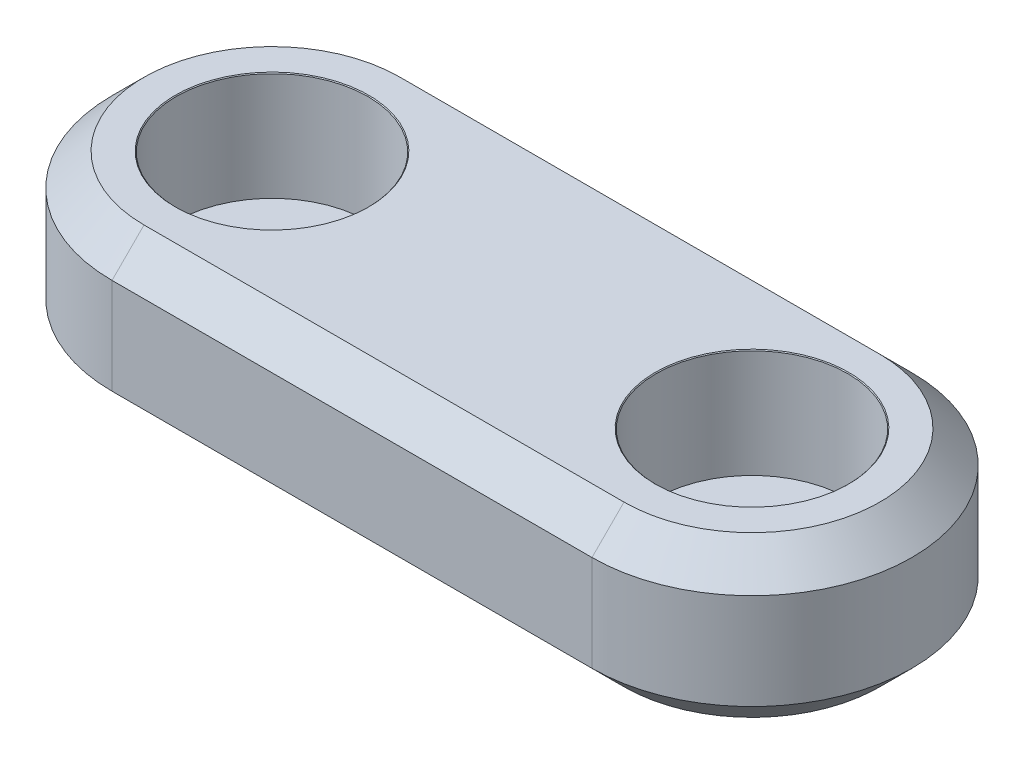
SolidWorks part; units mm, degrees
material "6061 Alloy"
ref_plane "Front Plane" through (0, 0, 0) normal (0, 0, 1) x (1, 0, 0)
ref_plane "Top Plane" through (0, 0, 0) normal (0, 1, 0) x (1, 0, 0)
ref_plane "Right Plane" through (0, 0, 0) normal (1, 0, 0) x (0, 0, -1)
sketch "Sketch1" plane through (0, 0, 0) normal (0, 1, 0) x (1, 0, 0)
  line L0 (-7.5, 0) -> (7.5, 0) construction
  line L1 (-7.5, 5) -> (7.5, 5)
  line L2 (-7.5, -5) -> (7.5, -5)
  arc A0 (-7.5, 5) -> (-7.5, -5) centre (-7.5, 0) ccw
  arc A1 (7.5, -5) -> (7.5, 5) centre (7.5, 0) ccw
  point P2 (0, 0)
  dimension "D2" = 5
  dimension "D1" = 15
extrude "Boss-Extrude1" add sketch "Sketch1" along normal blind 5
sketch "Sketch2" plane through (0, 5, 0) normal (0, 1, 0) x (1, 0, 0)
  arc A0 (-7.5, 5) -> (-7.5, -5) centre (-7.5, 0) ccw construction
  arc A1 (7.5, -5) -> (7.5, 5) centre (7.5, 0) ccw construction
  point P0 (-7.5, 0)
  point P1 (7.5, 0)
hole_wizard "CBORE for M3 Hexagon socket head cap screws1" positions "3DSketch1" profile "Sketch3" counterbore size "M3" standard "GB" end condition through all
sketch3d "3DSketch1"
  point P0 (-7.5, 5, 0)
  point P3 (7.5, 5, 0)
sketch "Sketch3" plane through (-7.5, 5, 0) normal (1, 0, 0) x (0, 0, 1)
  line L0 (0, 0) -> (0, 5)
  line L1 (0, 5) -> (1.6, 5)
  line L3 (1.6, 5) -> (1.6, 3.4)
  line L4 (3, 3.4) -> (1.6, 3.4)
  line L5 (3, 3.4) -> (3, 0.025)
  line L6 (3, 0.025) -> (3.025, 0)
  line L7 (3.025, 0) -> (0, 0)
  line L8 (-3, 0.025) -> (-3.025, 0) construction
  line L11 (0, -6.35) -> (0, 107.95) construction
  dimension "Thru Hole Dia." = 3.2
  dimension "Thru Hole Depth" = 5
  dimension "C'Bore Dia." = 6
  dimension "C'Bore Depth" = 3.4
  dimension "Near C'Sink Dia." = 6.05
  dimension "Near C'Sink Angle" = 90
chamfer "Chamfer1" distance 1 angle 45 8 edges at (0, 0, 5) (12.5, 0, 0) (-12.5, 0, 0) (0, 0, -5) (0, 5, 5) (12.5, 5, 0) (-12.5, 5, 0) (0, 5, -5)
